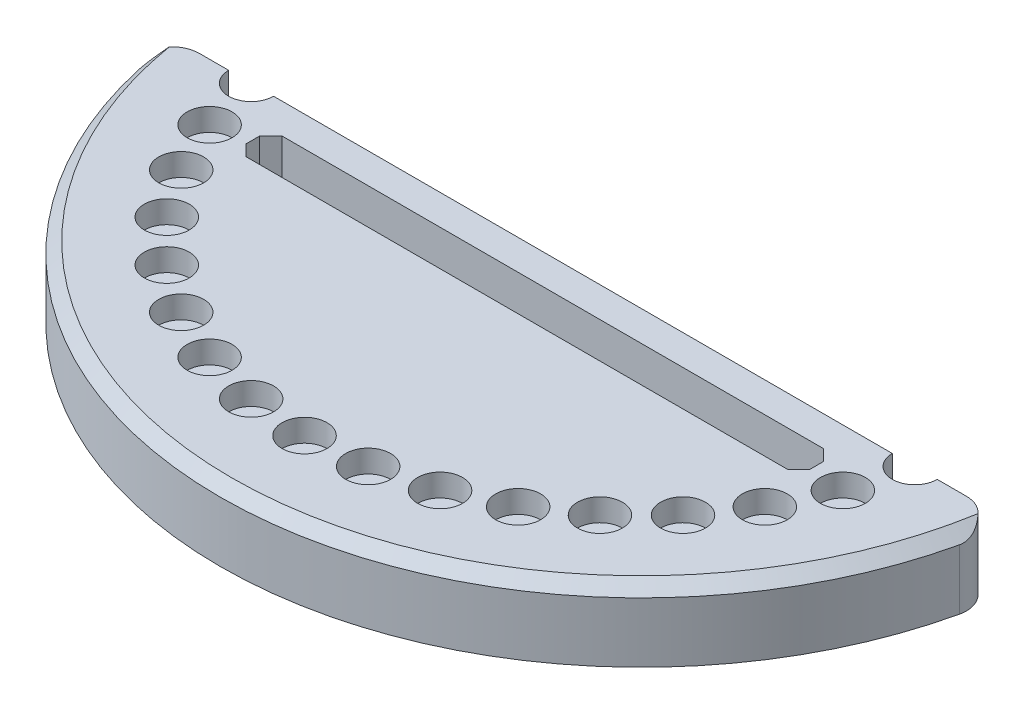
SolidWorks part; units mm, degrees
ref_plane "Front Plane" through (0, 0, 0) normal (0, 0, 1) x (1, 0, 0)
ref_plane "Top Plane" through (0, 0, 0) normal (0, 1, 0) x (1, 0, 0)
ref_plane "Right Plane" through (0, 0, 0) normal (1, 0, 0) x (0, 0, -1)
sketch "Sketch1" plane through (0, 0, 0) normal (0, 1, 0) x (1, 0, 0)
  circle A0 centre (0, 0) radius 37.5
  dimension "D1" = 75
extrude "Boss-Extrude1" add sketch "Sketch1" along normal blind 6.35
sketch "Sketch2" plane through (0, 6.35, 0) normal (0, 1, 0) x (1, 0, 0)
  circle A0 centre (0, 0) radius 30 construction
  circle A1 centre (0, 30) radius 2
  circle A2 centre (5.2094, 29.5442) radius 2
  circle A3 centre (10.2606, 28.1908) radius 2
  circle A4 centre (15, 25.9808) radius 2
  circle A5 centre (19.2836, 22.9813) radius 2
  circle A6 centre (22.9813, 19.2836) radius 2
  circle A7 centre (25.9808, 15) radius 2
  circle A8 centre (28.1908, 10.2606) radius 2
  circle A9 centre (29.5442, 5.2094) radius 2
  circle A10 centre (30, 0) radius 2
  circle A11 centre (29.5442, -5.2094) radius 2
  circle A12 centre (28.1908, -10.2606) radius 2
  circle A13 centre (25.9808, -15) radius 2
  circle A14 centre (22.9813, -19.2836) radius 2
  circle A15 centre (19.2836, -22.9813) radius 2
  circle A16 centre (15, -25.9808) radius 2
  circle A17 centre (10.2606, -28.1908) radius 2
  circle A18 centre (5.2094, -29.5442) radius 2
  circle A19 centre (0, -30) radius 2
  circle A20 centre (-5.2094, -29.5442) radius 2
  circle A21 centre (-10.2606, -28.1908) radius 2
  circle A22 centre (-15, -25.9808) radius 2
  circle A23 centre (-19.2836, -22.9813) radius 2
  circle A24 centre (-22.9813, -19.2836) radius 2
  circle A25 centre (-25.9808, -15) radius 2
  circle A26 centre (-28.1908, -10.2606) radius 2
  circle A27 centre (-29.5442, -5.2094) radius 2
  circle A28 centre (-30, 0) radius 2
  circle A29 centre (-29.5442, 5.2094) radius 2
  circle A30 centre (-28.1908, 10.2606) radius 2
  circle A31 centre (-25.9808, 15) radius 2
  circle A32 centre (-22.9813, 19.2836) radius 2
  circle A33 centre (-19.2836, 22.9813) radius 2
  circle A34 centre (-15, 25.9808) radius 2
  circle A35 centre (-10.2606, 28.1908) radius 2
  circle A36 centre (-5.2094, 29.5442) radius 2
  point P77 (0, 0)
  dimension "D1" = 60
  dimension "D2" = 4
  dimension "D3" = 36
extrude "Cut-Extrude1" cut sketch "Sketch2" against normal blind 2
hole_wizard "M6x1.0 Tapped Hole1" positions "Sketch4" profile "Sketch5" tap size "M6x1.0" standard "ANSI Metric"
sketch "Sketch4" plane through (0, 6.35, 0) normal (0, 1, 0) x (1, 0, 0)
  point P0 (0, 0)
sketch "Sketch5" plane through (0, 6.35, 0) normal (1, 0, 0) x (0, 0, 1)
  line L0 (0, 0) -> (0, 16.5022)
  line L1 (0, 16.5022) -> (2.5, 15)
  line L2 (2.5, 15) -> (2.5, 0)
  line L5 (2.5, 0) -> (0, 0)
  line L10 (0, 16.5022) -> (-2.5, 15) construction
  line L11 (0, -6.35) -> (0, 107.95) construction
  dimension "Tap Drill Dia." = 5
  dimension "Tap Drill Depth" = 15
  dimension "Drill Angle" = 118
cosmetic thread "Hole Thread1" parameters "D1"=12, "D2"=6
chamfer "Chamfer1" distance 1 angle 45 1 edges at (0, 6.35, 37.5)
sketch "Sketch6" plane through (0, 6.35, 0) normal (0, 1, 0) x (1, 0, 0)
  line L1 (-25.1, -7.9) -> (25.1, -7.9)
  line L2 (-25.1, -7.9) -> (-25.1, -11.1)
  line L3 (-25.1, -11.1) -> (25.1, -11.1)
  line L4 (25.1, -7.9) -> (25.1, -11.1)
  line L5 (-25.1, -7.9) -> (25.1, -11.1) construction
  line L6 (-25.1, -11.1) -> (25.1, -7.9) construction
  point P0 (0, -9.5)
  dimension "D1" = 3.2
  dimension "D2" = 50.2
  dimension "D3" = 7.9
extrude "Cut-Extrude2" cut sketch "Sketch6" against normal blind 10
chamfer "Chamfer2" distance 1 angle 45 4 edges at (-25.1, 3.175, 7.9) (-25.1, 3.175, 11.1) (25.1, 3.175, 11.1) (25.1, 3.175, 7.9)
sketch "Sketch7" plane through (0, 6.35, 0) normal (0, 1, 0) x (1, 0, 0)
  line L0 (-29.5442, -5.2094) -> (-45.4053, -5.2094)
  line L1 (-45.4053, -5.2094) -> (48.2028, -5.2094)
  line L2 (48.2028, -5.2094) -> (48.2028, 45.0761)
  line L3 (48.2028, 45.0761) -> (-45.4053, 43.5698)
  line L4 (-45.4053, 43.5698) -> (-45.4053, -5.2094)
  circle M13 centre (0, 0) radius 36.5
  circle M14 centre (0, 0) radius 2.5
  circle M15 centre (-22.9813, 19.2836) radius 2
  circle M16 centre (-19.2836, 22.9813) radius 2
  circle M17 centre (-25.9808, 15) radius 2
  circle M18 centre (-28.1908, 10.2606) radius 2
  circle M19 centre (-29.5442, 5.2094) radius 2
  circle M20 centre (-30, 0) radius 2
  circle M21 centre (-29.5442, -5.2094) radius 2
  circle M37 centre (29.5442, -5.2094) radius 2
  circle M38 centre (30, 0) radius 2
  circle M39 centre (5.2094, 29.5442) radius 2
  circle M40 centre (10.2606, 28.1908) radius 2
  circle M41 centre (15, 25.9808) radius 2
  circle M42 centre (19.2836, 22.9813) radius 2
  circle M43 centre (22.9813, 19.2836) radius 2
  circle M44 centre (25.9808, 15) radius 2
  circle M45 centre (28.1908, 10.2606) radius 2
  circle M46 centre (29.5442, 5.2094) radius 2
  circle M47 centre (-15, 25.9808) radius 2
  circle M48 centre (-10.2606, 28.1908) radius 2
  circle M49 centre (-5.2094, 29.5442) radius 2
  circle M50 centre (0, 30) radius 2
extrude "Cut-Extrude3" cut sketch "Sketch7" against normal blind 18 contours L3 L4 L0 L1 L2 M13 | L0 L1 M21 | M20 | M19 | M18 | M17 | L1 L0 M21 M37 M13 M15 M17 M19 M39 M41 M43 M45 M47 M49 M50 M48 M46 M44 M42 M40 M38 M20 M18 M16 M14 | M15 | M16 | M47 | M48 | M49 | M50 | M39 | M40 | M41 | M42 | M43 | M44 | M45 | M46 | M38 | L1 M37
fillet "Fillet1" radius 2.5 2 edges at (37.1364, 2.675, 5.2094) (-37.1364, 2.675, 5.2094)
